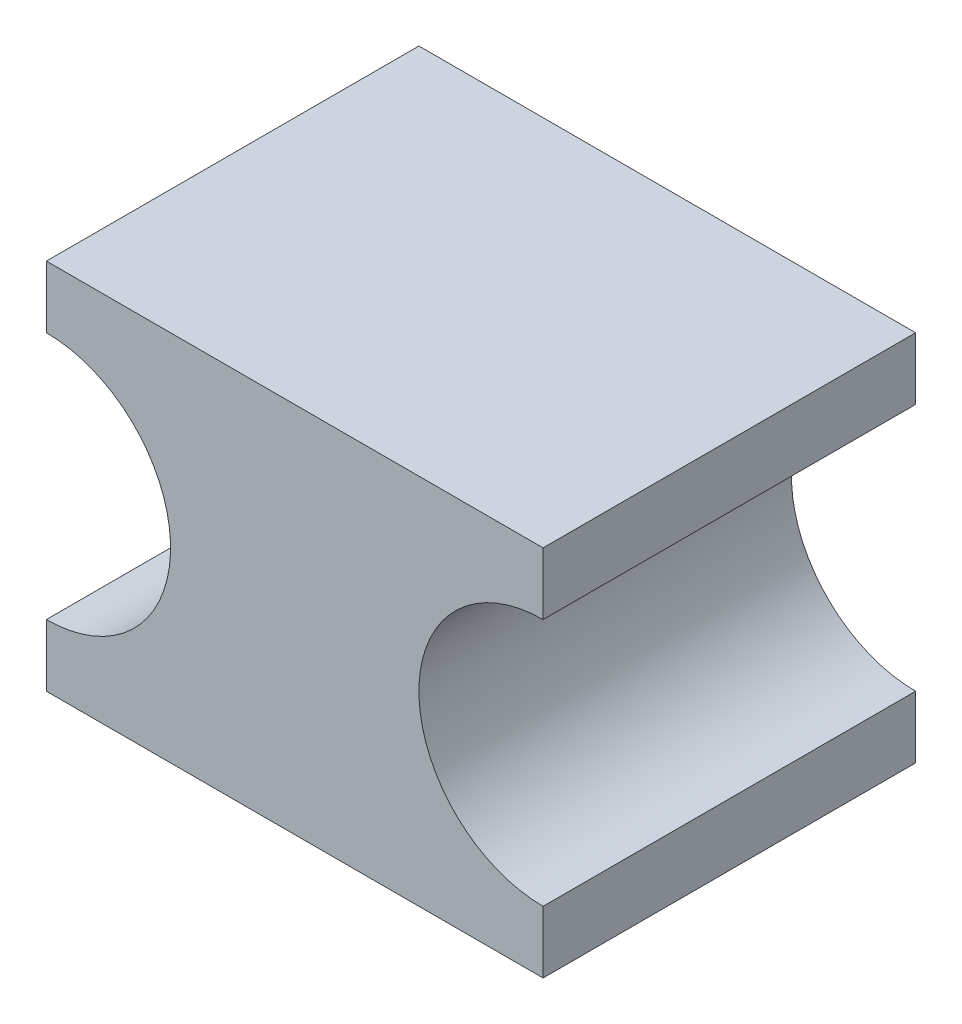
SolidWorks part; units mm, degrees
ref_plane "Front Plane" through (0, 0, 0) normal (0, 0, 1) x (1, 0, 0)
ref_plane "Top Plane" through (0, 0, 0) normal (0, 1, 0) x (1, 0, 0)
ref_plane "Right Plane" through (0, 0, 0) normal (1, 0, 0) x (0, 0, -1)
sketch "Sketch1" plane through (0, 0, 0) normal (0, 1, 0) x (1, 0, 0)
  line L1 (0, 0) -> (50.8, 0)
  line L2 (0, 0) -> (0, 38.1)
  line L3 (0, 38.1) -> (50.8, 38.1)
  line L4 (50.8, 0) -> (50.8, 38.1)
  dimension "D1" = 50.8
  dimension "D2" = 38.1
extrude "Boss-Extrude1" add sketch "Sketch1" along normal blind 38.1
sketch "Sketch2" plane through (0, 0, 0) normal (0, 0, 1) x (1, 0, 0)
  line L0 (0, 38.1) -> (0, 0) construction
  line L1 (50.8, 38.1) -> (50.8, 0) construction
  circle A0 centre (0, 19.05) radius 12.7
  circle A1 centre (50.8, 19.05) radius 12.7
  dimension "D1" = 25.4
  dimension "D2" = 25.4
extrude "Cut-Extrude1" cut sketch "Sketch2" against normal blind 38.1
